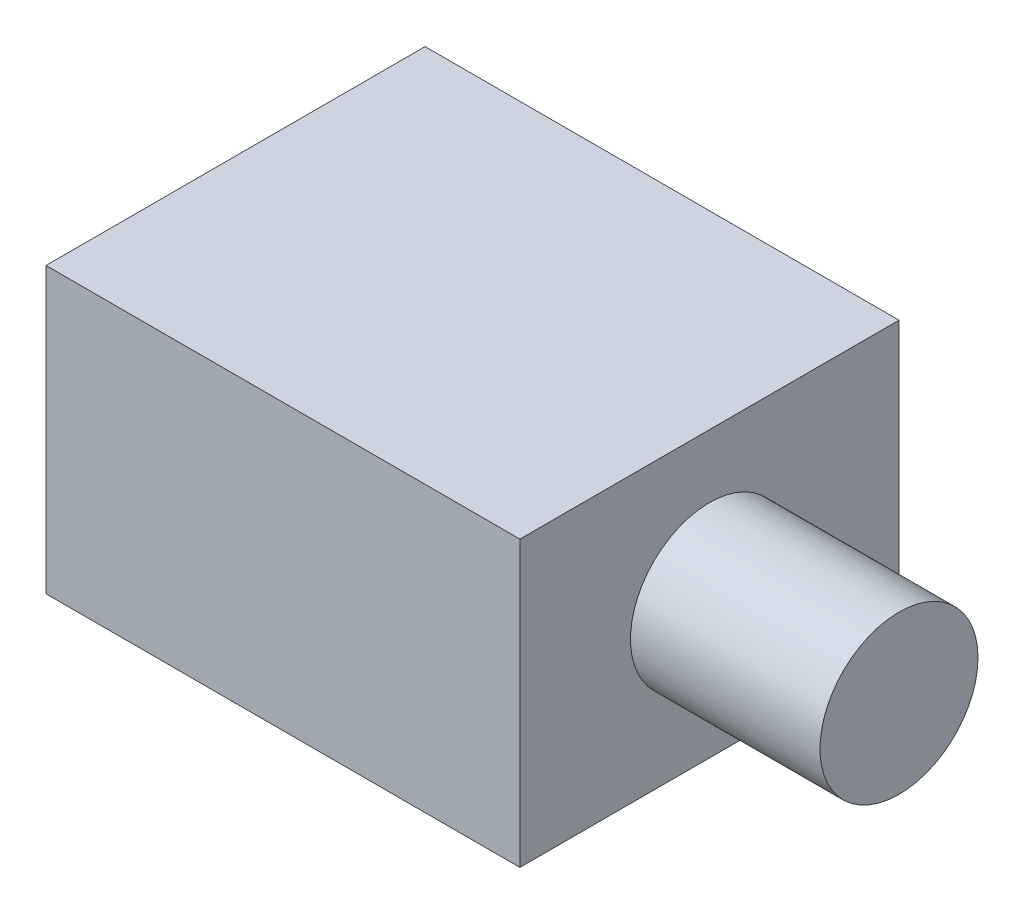
SolidWorks part; units mm, degrees
ref_plane "前视基准面" through (0, 0, 0) normal (0, 0, 1) x (1, 0, 0)
ref_plane "上视基准面" through (0, 0, 0) normal (0, 1, 0) x (1, 0, 0)
ref_plane "右视基准面" through (0, 0, 0) normal (1, 0, 0) x (0, 0, -1)
sketch "草图1" plane through (0, 0, 0) normal (0, 1, 0) x (1, 0, 0)
  line L0 (-30, 24) -> (30, 24)
  line L1 (30, 24) -> (30, -24)
  line L2 (30, -24) -> (-30, -24)
  line L3 (-30, -24) -> (-30, 24)
extrude "凸台-拉伸1" add sketch "草图1" along normal blind 36
ref_plane "基准面1" through (54, 0, 0) normal (1, 0, 0) x (0, 0, -1)
ref_plane "基准面2" through (30, 0, 0) normal (1, 0, 0) x (0, 0, -1)
sketch "草图2" plane through (54, 0, 0) normal (1, 0, 0) x (0, 0, -1)
  circle A0 centre (0, 18) radius 10
extrude "凸台-拉伸2" add sketch "草图2" against normal up to surface (24 mm away) up to plane "基准面2"
